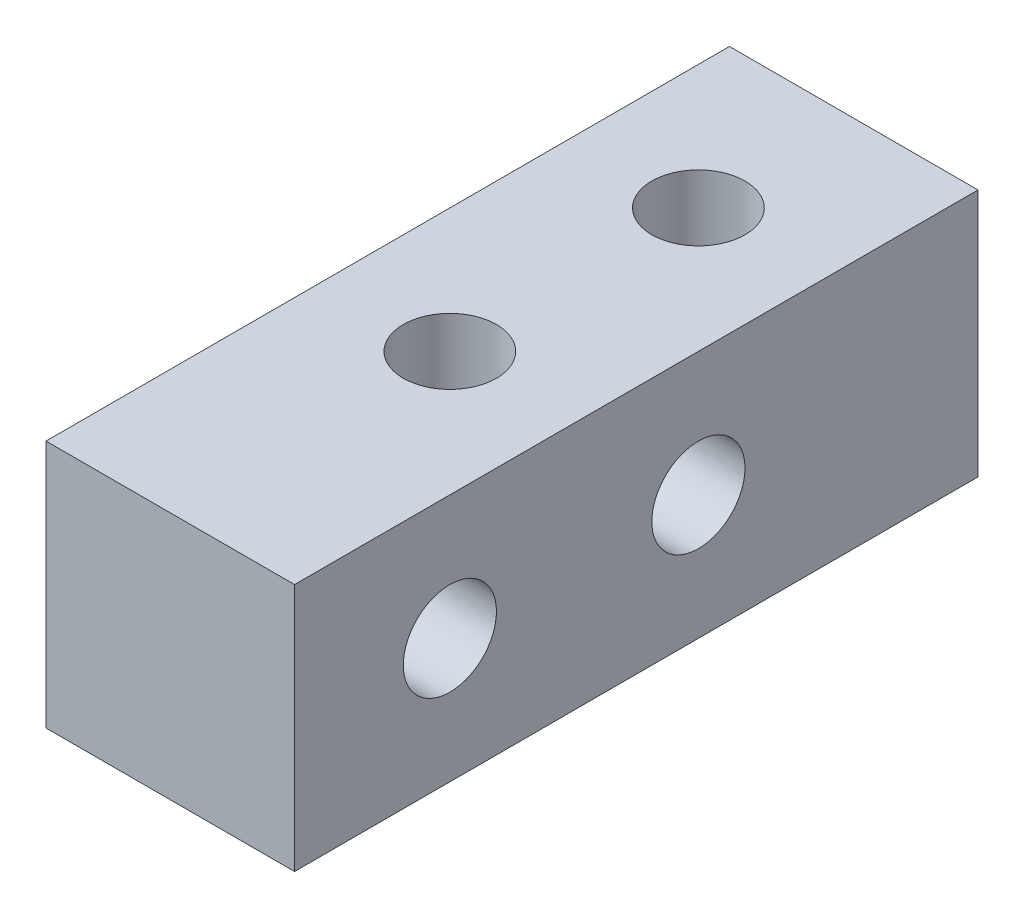
SolidWorks part; units mm, degrees
ref_plane "前视基准面" through (0, 0, 0) normal (0, 0, 1) x (1, 0, 0)
ref_plane "上视基准面" through (0, 0, 0) normal (0, 1, 0) x (1, 0, 0)
ref_plane "右视基准面" through (0, 0, 0) normal (1, 0, 0) x (0, 0, -1)
sketch "草图1" plane through (0, 0, 0) normal (0, 0, 1) x (1, 0, 0)
  line L1 (4, -4) -> (-4, -4)
  line L2 (4, -4) -> (4, 4)
  line L3 (4, 4) -> (-4, 4)
  line L4 (-4, -4) -> (-4, 4)
  line L5 (4, -4) -> (-4, 4) construction
  line L6 (4, 4) -> (-4, -4) construction
  point P0 (0, 0)
  dimension "D1" = 8
  dimension "D2" = 8
extrude "凸台-拉伸1" add sketch "草图1" along normal blind 22
sketch "草图2" plane through (4, 0, 0) normal (1, 0, 0) x (0, 0, -1)
  line L0 (0, 0) -> (-22, 0) construction
  line L1 (-22, -4) -> (-22, 4) construction
  circle A0 centre (-17, 0) radius 1.5
  circle A1 centre (-9, 0) radius 1.5
  dimension "D1" = 3
  dimension "D2" = 3
  dimension "D3" = 5
  dimension "D4" = 8
extrude "切除-拉伸1" cut sketch "草图2" against normal through all
sketch "草图3" plane through (0, 4, 0) normal (0, 1, 0) x (1, 0, 0)
  line L0 (0, 0) -> (0, -22) construction
  line L1 (4, -22) -> (-4, -22) construction
  circle A0 centre (0, -5) radius 1.5
  circle A1 centre (0, -13) radius 1.5
  dimension "D1" = 3
  dimension "D4" = 3
  dimension "D2" = 5
  dimension "D3" = 8
extrude "切除-拉伸2" cut sketch "草图3" against normal blind 22
